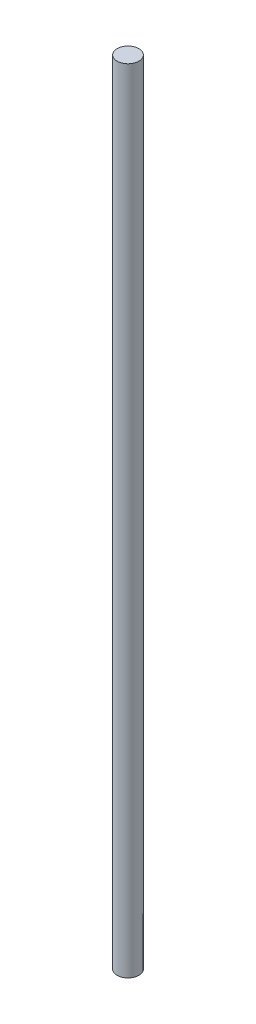
SolidWorks part; units mm, degrees
ref_plane "前视基准面" through (0, 0, 0) normal (0, 0, 1) x (1, 0, 0)
ref_plane "上视基准面" through (0, 0, 0) normal (0, 1, 0) x (1, 0, 0)
ref_plane "右视基准面" through (0, 0, 0) normal (1, 0, 0) x (0, 0, -1)
sketch "草图1" plane through (0, 0, 0) normal (0, 1, 0) x (1, 0, 0)
  circle A0 centre (0, 0) radius 11
  dimension "D1" = 22
extrude "凸台-拉伸1" add sketch "草图1" along normal blind 800
